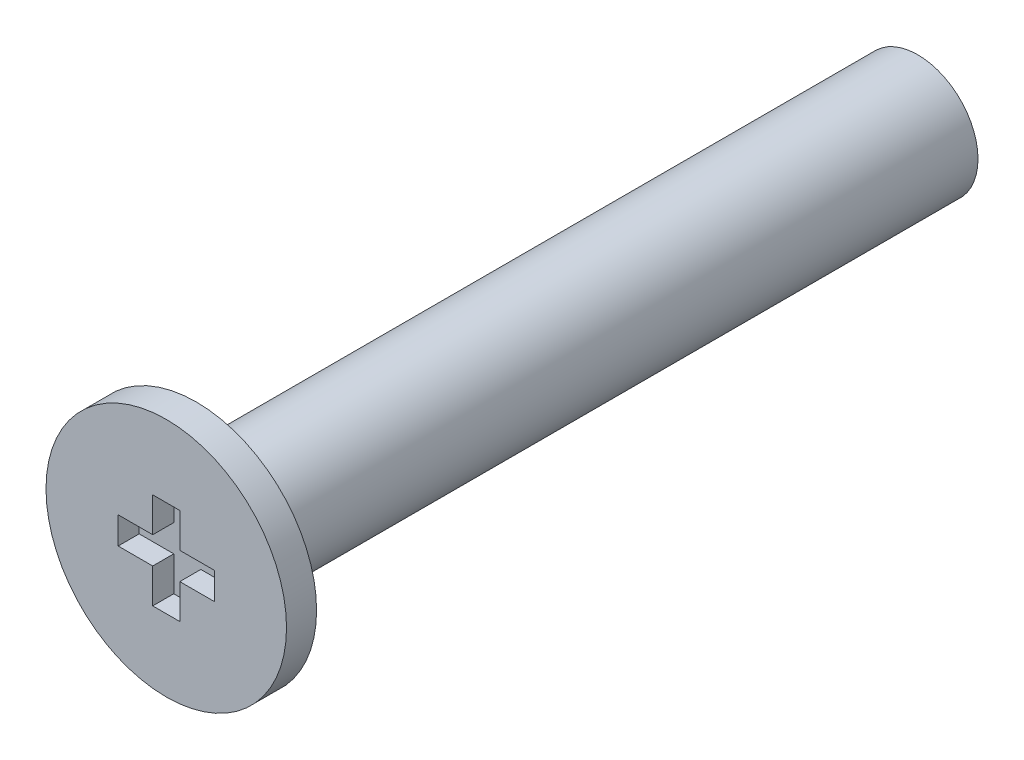
SolidWorks part; units mm, degrees
ref_plane "前视基准面" through (0, 0, 0) normal (0, 0, 1) x (1, 0, 0)
ref_plane "上视基准面" through (0, 0, 0) normal (0, 1, 0) x (1, 0, 0)
ref_plane "右视基准面" through (0, 0, 0) normal (1, 0, 0) x (0, 0, -1)
other "Configuration Table"
sketch "草图1" plane through (0, 0, 0) normal (0, 0, 1) x (1, 0, 0)
  circle A0 centre (0, 0) radius 1
extrude "标准杆径_头下长度" add sketch "草图1" against normal blind 12
sketch "草图2" plane through (0, 0, 0) normal (0, 0, 1) x (1, 0, 0)
  circle A0 centre (0, 0) radius 1.9
sketch "草图4" plane through (0, 0, 0) normal (0, 1, 0) x (1, 0, 0)
  line L0 (0, 0) -> (2.25, 0)
  line L1 (2.25, 0) -> (2.25, -0.1843)
  line L2 (0, -1.2) -> (0, 0)
  line L3 (0, 2) -> (0, -3.2) construction
  arc A0 (2.25, -0.1843) -> (0, -1.2) centre (0, 1.8) cw
sketch "草图5" plane through (0, 0, 0) normal (0, 0, 1) x (1, 0, 0)
  line L0 (-0.3, -1.1) -> (0.3, -1.1)
  line L1 (0.3, -1.1) -> (0.3, -0.3)
  line L2 (0.3, -0.3) -> (1.1, -0.3)
  line L3 (1.1, -0.3) -> (1.1, 0.3)
  line L4 (1.1, 0.3) -> (0.3, 0.3)
  line L5 (0.3, 0.3) -> (0.3, 1.1)
  line L6 (0.3, 1.1) -> (-0.3, 1.1)
  line L7 (-0.3, 1.1) -> (-0.3, 0.3)
  line L8 (-0.3, 0.3) -> (-1.1, 0.3)
  line L9 (-1.1, 0.3) -> (-1.1, -0.3)
  line L10 (-1.1, -0.3) -> (-0.3, -0.3)
  line L11 (-0.3, -0.3) -> (-0.3, -1.1)
sketch "草图6" plane through (0, 0, 0) normal (0, 1, 0) x (1, 0, 0)
  line L0 (0, 0) -> (1.75, 0)
  line L1 (1.75, 0) -> (1.75, -0.5854)
  line L2 (0, -1.3) -> (0, 0)
  line L3 (0, 2) -> (0, -3.3) construction
  arc A0 (1.75, -0.5854) -> (0, -1.3) centre (0, 1.2) cw
sketch "草图7" plane through (0, 0, 0) normal (0, 0, 1) x (1, 0, 0)
  line L0 (-0.3, -1.1) -> (0.3, -1.1)
  line L1 (0.3, -1.1) -> (0.3, -0.3)
  line L2 (0.3, -0.3) -> (1.1, -0.3)
  line L3 (1.1, -0.3) -> (1.1, 0.3)
  line L4 (1.1, 0.3) -> (0.3, 0.3)
  line L5 (0.3, 0.3) -> (0.3, 1.1)
  line L6 (0.3, 1.1) -> (-0.3, 1.1)
  line L7 (-0.3, 1.1) -> (-0.3, 0.3)
  line L8 (-0.3, 0.3) -> (-1.1, 0.3)
  line L9 (-1.1, 0.3) -> (-1.1, -0.3)
  line L10 (-1.1, -0.3) -> (-0.3, -0.3)
  line L11 (-0.3, -0.3) -> (-0.3, -1.1)
sketch "草图8" plane through (0, 0, 0) normal (0, 1, 0) x (1, 0, 0)
  line L0 (0, 0) -> (2, 0)
  line L1 (2, 0) -> (2, -0.5)
  line L2 (2, -0.5) -> (0, -0.5)
  line L3 (0, -0.5) -> (0, 0)
  line L4 (0, 2) -> (0, -2.5) construction
revolve "已确认_十字槽超薄头" add sketch "草图8" angle 360 about L4
sketch "草图9" plane through (0, 0, 0) normal (0, 0, 1) x (1, 0, 0)
  line L0 (-0.225, -0.8) -> (0.225, -0.8)
  line L1 (0.225, -0.8) -> (0.225, -0.225)
  line L2 (0.225, -0.225) -> (0.8, -0.225)
  line L3 (0.8, -0.225) -> (0.8, 0.225)
  line L4 (0.8, 0.225) -> (0.225, 0.225)
  line L5 (0.225, 0.225) -> (0.225, 0.8)
  line L6 (0.225, 0.8) -> (-0.225, 0.8)
  line L7 (-0.225, 0.8) -> (-0.225, 0.225)
  line L8 (-0.225, 0.225) -> (-0.8, 0.225)
  line L9 (-0.8, 0.225) -> (-0.8, -0.225)
  line L10 (-0.8, -0.225) -> (-0.225, -0.225)
  line L11 (-0.225, -0.225) -> (-0.225, -0.8)
extrude "十字槽_PH0_简化" cut sketch "草图9" against normal blind 0.36 from offset 0.51
